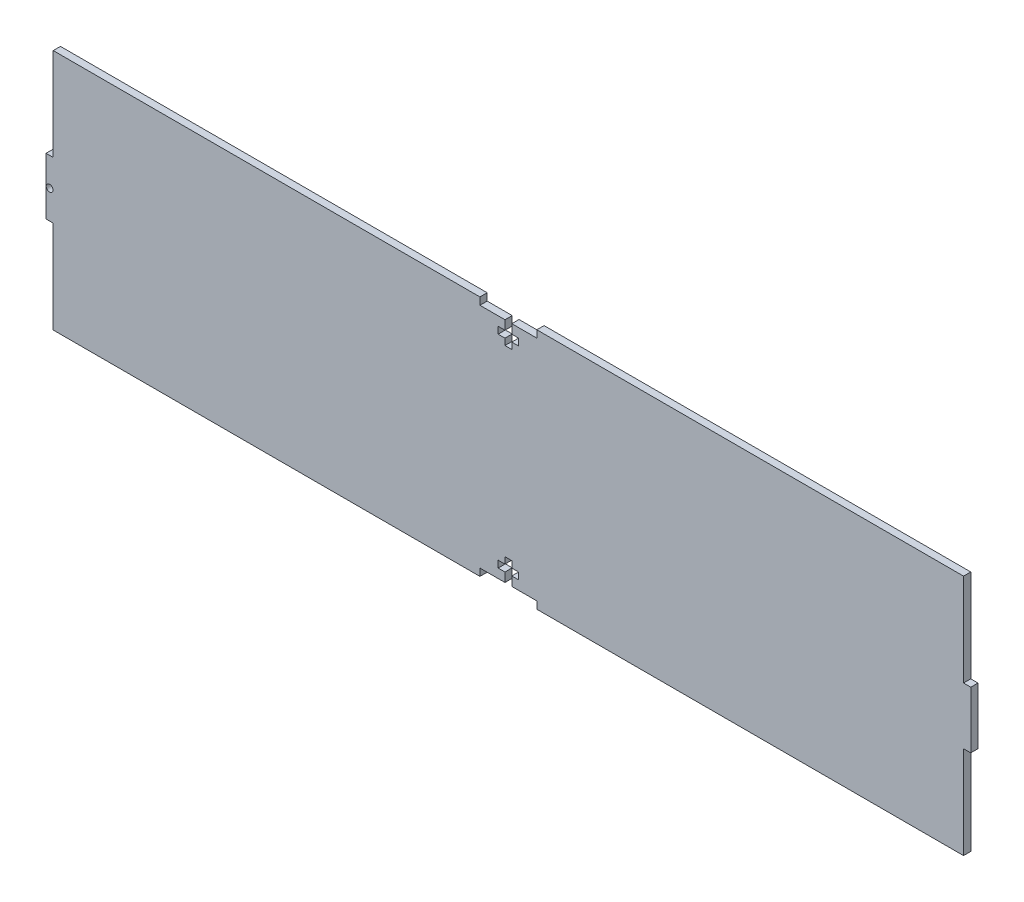
SolidWorks part; units mm, degrees
ref_plane "Front Plane" through (0, 0, 0) normal (0, 0, 1) x (1, 0, 0)
ref_plane "Top Plane" through (0, 0, 0) normal (0, 1, 0) x (1, 0, 0)
ref_plane "Right Plane" through (0, 0, 0) normal (1, 0, 0) x (0, 0, -1)
sketch "Sketch1" plane through (0, 0, 0) normal (0, 0, 1) x (1, 0, 0)
  line L0 (-300, 0) -> (300, 0) construction
  line L1 (-200, 53.18) -> (-12.5, 53.18)
  line L2 (-200, 53.18) -> (-200, 12.5)
  line L3 (-200, -53.18) -> (-12.5, -53.18)
  line L5 (-200, 53.18) -> (200, -53.18) construction
  line L6 (-200, -53.18) -> (200, 53.18) construction
  line L7 (-203.18, 12.5) -> (-200, 12.5)
  line L8 (-203.18, 12.5) -> (-203.18, -12.5)
  line L9 (-203.18, -12.5) -> (-200, -12.5)
  line L11 (-203.18, 12.5) -> (-200, -12.5) construction
  line L12 (-203.18, -12.5) -> (-200, 12.5) construction
  line L13 (0, 40.18) -> (0, -40.18) construction
  line L14 (-203.18, 0) -> (-300, 0) construction
  line L15 (-200, -12.5) -> (-200, -53.18)
  line L20 (1.5, -43) -> (4.5, -43)
  line L21 (-12.5, -50) -> (-1.5, -50)
  line L22 (-12.5, -50) -> (-12.5, -53.18)
  line L24 (12.5, -50) -> (12.5, -53.18)
  line L25 (-12.5, -50) -> (12.5, -53.18) construction
  line L26 (-12.5, -53.18) -> (12.5, -50) construction
  line L31 (-1.5, -40.18) -> (1.5, -40.18)
  line L32 (-1.5, -40.18) -> (-1.5, -43)
  line L33 (-4.5, -43) -> (-1.5, -43)
  line L34 (-4.5, -43) -> (-4.5, -46)
  line L35 (-4.5, -46) -> (-1.5, -46)
  line L36 (4.5, -43) -> (4.5, -46)
  line L37 (1.5, -50) -> (12.5, -50)
  line L38 (1.5, 46) -> (1.5, 50)
  line L40 (1.5, -40.18) -> (1.5, -43)
  line L41 (1.5, 46) -> (4.5, 46)
  line L42 (4.5, 43) -> (4.5, 46)
  line L43 (12.5, -53.18) -> (200, -53.18)
  line L47 (200, 53.18) -> (200, 12.5)
  line L49 (-1.5, -46) -> (-1.5, -50)
  line L50 (1.5, -46) -> (4.5, -46)
  line L51 (1.5, -46) -> (1.5, -50)
  line L52 (1.5, 43) -> (4.5, 43)
  line L53 (1.5, 40.18) -> (1.5, 43)
  line L54 (-1.5, 40.18) -> (1.5, 40.18)
  line L55 (-1.5, 40.18) -> (-1.5, 43)
  line L56 (-4.5, 43) -> (-1.5, 43)
  line L57 (-4.5, 43) -> (-4.5, 46)
  line L58 (-4.5, 46) -> (-1.5, 46)
  line L59 (-1.5, 46) -> (-1.5, 50)
  line L60 (-12.5, 50) -> (-1.5, 50)
  line L61 (-12.5, 50) -> (-12.5, 53.18)
  line L63 (12.5, 50) -> (12.5, 53.18)
  line L64 (1.5, 50) -> (12.5, 50)
  line L65 (12.5, 53.18) -> (200, 53.18)
  line L67 (203.18, 12.5) -> (200, 12.5)
  line L68 (203.18, 12.5) -> (203.18, -12.5)
  line L69 (203.18, -12.5) -> (200, -12.5)
  line L71 (203.18, 12.5) -> (200, -12.5) construction
  line L72 (203.18, -12.5) -> (200, 12.5) construction
  line L73 (200, -12.5) -> (200, -53.18)
  circle A0 centre (-201.59, 0) radius 1.5
  point P0 (0, 0)
  point P6 (-201.59, 0)
  point P18 (304.6854, 0)
  point P19 (201.59, 0)
  point P24 (0, -51.59)
  point P29 (0, -43.7195)
  point P30 (0, -45.09)
  point P34 (0, -44.5)
  point P60 (0, 0)
  dimension "D5" = 3
  dimension "D1" = 400
  dimension "D2" = 106.36
  dimension "D3" = 3.18
  dimension "D4" = 25
  dimension "D6" = 3
  dimension "D7" = 3
  dimension "D8" = 4
  dimension "D9" = 13
  dimension "D10" = 3.18
  dimension "D11" = 9
  dimension "D12" = 25
  dimension "D13" = 25
  dimension "D14" = 3.18
extrude "Boss-Extrude1" add sketch "Sketch1" along normal blind 3.18
